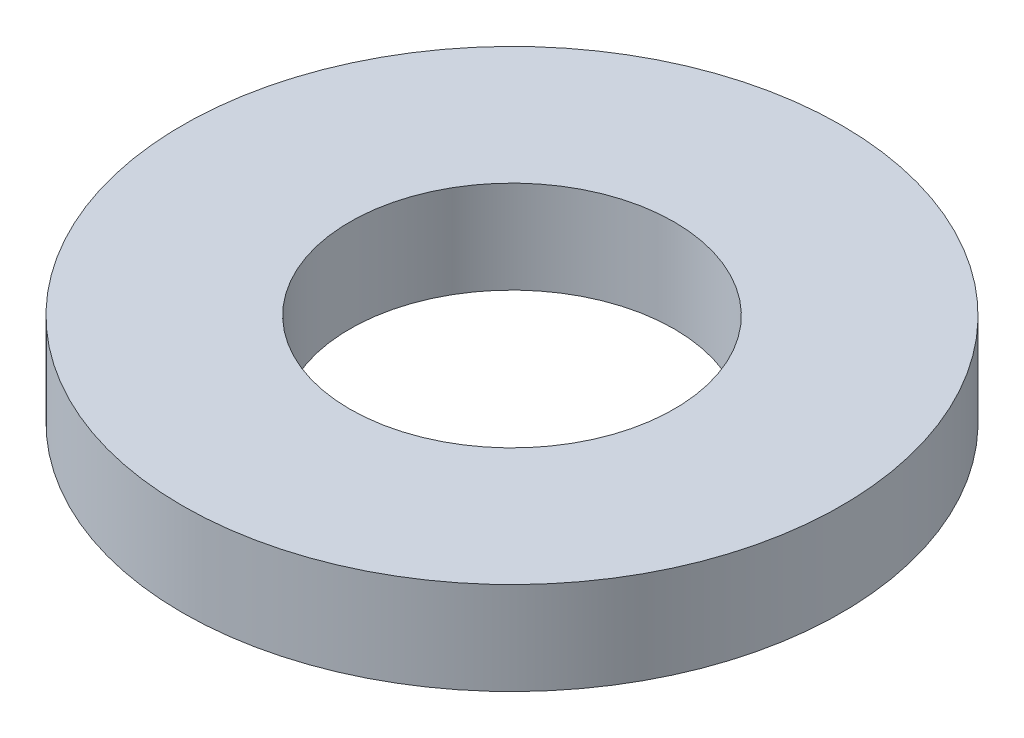
SolidWorks part; units mm, degrees
ref_plane "Front Plane" through (0, 0, 0) normal (0, 0, 1) x (1, 0, 0)
ref_plane "Top Plane" through (0, 0, 0) normal (0, 1, 0) x (1, 0, 0)
ref_plane "Right Plane" through (0, 0, 0) normal (1, 0, 0) x (0, 0, -1)
sketch "Sketch1" plane through (0, 0, 0) normal (0, 1, 0) x (1, 0, 0)
  circle A0 centre (0, 0) radius 28.45
  dimension "D1" = 56.9
extrude "Boss-Extrude1" add sketch "Sketch1" along normal blind 8
sketch "Sketch2" plane through (0, 8, 0) normal (0, 1, 0) x (1, 0, 0)
  circle A0 centre (0, 0) radius 14
  dimension "D1" = 28
extrude "Cut-Extrude1" cut sketch "Sketch2" against normal through all
